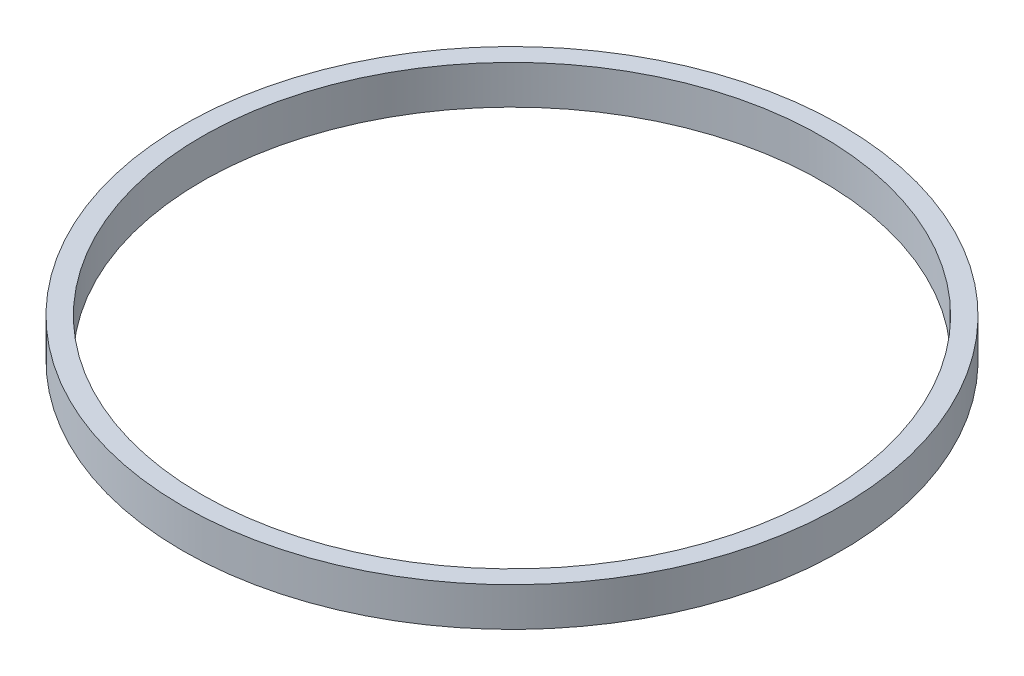
SolidWorks part; units mm, degrees
ref_plane "Ön Düzlem" through (0, 0, 0) normal (0, 0, 1) x (1, 0, 0)
ref_plane "Üst Düzlem" through (0, 0, 0) normal (0, 1, 0) x (1, 0, 0)
ref_plane "Sağ Düzlem" through (0, 0, 0) normal (1, 0, 0) x (0, 0, -1)
sketch "Çizim1" plane through (0, 0, 0) normal (0, 1, 0) x (1, 0, 0)
  circle A0 centre (0, 0) radius 80
  circle A1 centre (0, 0) radius 85
  dimension "D1" = 160
  dimension "D2" = 170
extrude "Yükseklik-Ekstrüzyon1" add sketch "Çizim1" along normal blind 10
